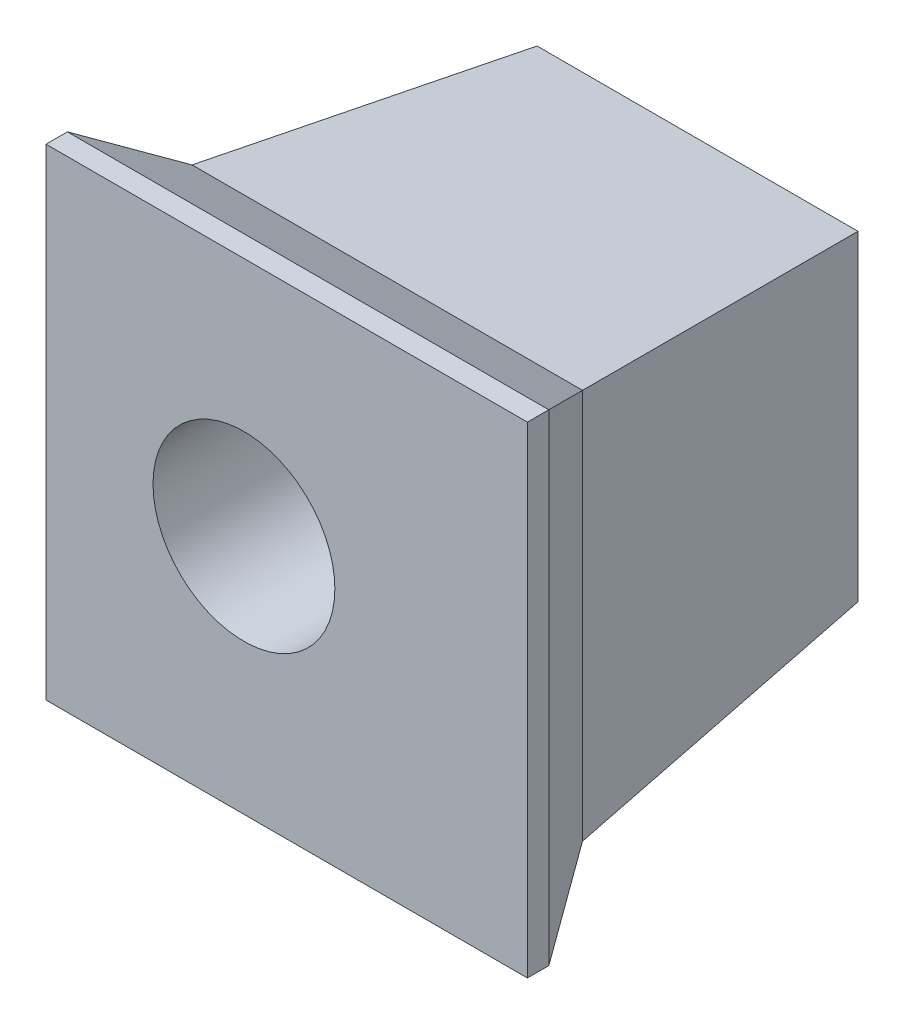
SolidWorks part; units mm, degrees
ref_plane "Front" through (0, 0, 0) normal (0, 0, 1) x (1, 0, 0)
ref_plane "Top" through (0, 0, 0) normal (0, 1, 0) x (1, 0, 0)
ref_plane "Right" through (0, 0, 0) normal (1, 0, 0) x (0, 0, -1)
sketch "草图1" plane through (0, 0, 0) normal (0, 0, 1) x (1, 0, 0)
  line L1 (-18.25, 18.25) -> (18.25, 18.25)
  line L2 (-18.25, 18.25) -> (-18.25, -18.25)
  line L3 (-18.25, -18.25) -> (18.25, -18.25)
  line L4 (18.25, 18.25) -> (18.25, -18.25)
  line L5 (-18.25, 18.25) -> (18.25, -18.25) construction
  line L6 (-18.25, -18.25) -> (18.25, 18.25) construction
  point P0 (0, 0)
  dimension "D1" = 36.5
  dimension "D2" = 36.5
ref_plane "基准面1" through (0, 0, 7.4) normal (0, 0, 1) x (1, 0, 0)
sketch "草图2" plane through (0, 0, 7.4) normal (0, 0, 1) x (1, 0, 0)
  line L1 (-22.5, 22.5) -> (22.5, 22.5)
  line L2 (-22.5, 22.5) -> (-22.5, -22.5)
  line L3 (-22.5, -22.5) -> (22.5, -22.5)
  line L4 (22.5, 22.5) -> (22.5, -22.5)
  line L5 (-22.5, 22.5) -> (22.5, -22.5) construction
  line L6 (-22.5, -22.5) -> (22.5, 22.5) construction
  point P0 (0, 0)
  dimension "D1" = 45
  dimension "D2" = 45
loft "放样1" add profiles "草图1", "草图2"
ref_plane "基准面2" through (0, 0, -29) normal (0, 0, -1) x (-1, 0, 0)
sketch "草图3" plane through (0, 0, -29) normal (0, 0, -1) x (-1, 0, 0)
  line L1 (-15, 15) -> (15, 15)
  line L2 (-15, 15) -> (-15, -15)
  line L3 (-15, -15) -> (15, -15)
  line L4 (15, 15) -> (15, -15)
  line L5 (-15, 15) -> (15, -15) construction
  line L6 (-15, -15) -> (15, 15) construction
  point P0 (0, 0)
  dimension "D1" = 30
  dimension "D2" = 30
loft "放样2" add profiles "草图3" section "草图3" section face at (0, 0, 0)
sketch "草图4" plane through (0, 0, 7.4) normal (0, 0, 1) x (1, 0, 0)
  circle A0 centre (-4, 0) radius 8.5
  dimension "D1" = 17
  dimension "D2" = 4
extrude "切除-拉伸1" cut sketch "草图4" against normal blind 33.4
sketch "草图5" plane through (0, 0, -26) normal (0, 0, 1) x (1, 0, 0)
  circle A0 centre (-4, 0) radius 3
  dimension "D1" = 6
extrude "切除-拉伸2" cut sketch "草图5" against normal blind 33.4
sketch "草图6" plane through (0, 0, 7.4) normal (0, 0, 1) x (1, 0, 0)
  line L4 (22.5, -22.5) -> (22.5, 22.5)
  line L5 (22.5, 22.5) -> (-22.5, 22.5)
  line L6 (-22.5, 22.5) -> (-22.5, -22.5)
  line L7 (-22.5, -22.5) -> (22.5, -22.5)
  line L8 (22.5, -22.5) -> (22.5, 22.5)
  line L9 (22.5, 22.5) -> (-22.5, 22.5)
  line L10 (-22.5, 22.5) -> (-22.5, -22.5)
  line L11 (-22.5, -22.5) -> (22.5, -22.5)
  circle A0 centre (-4, 0) radius 8.5 construction
  circle A1 centre (-4, 0) radius 8.5
  dimension "D1" = 0
extrude "凸台-拉伸1" add sketch "草图6" along normal blind 2
